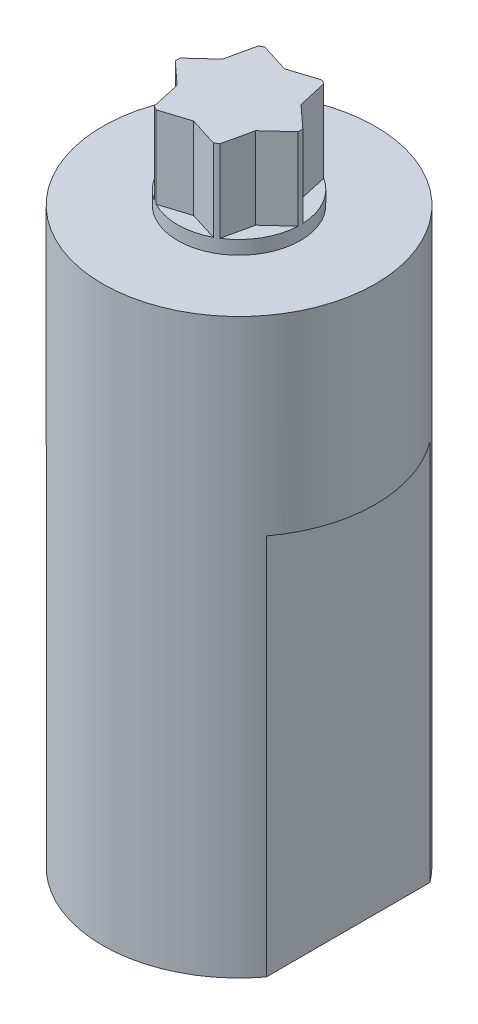
SolidWorks part; units mm, degrees
material "BUTYL"
ref_plane "Front Plane" through (0, 0, 0) normal (0, 0, 1) x (1, 0, 0)
ref_plane "Top Plane" through (0, 0, 0) normal (0, 1, 0) x (1, 0, 0)
ref_plane "Right Plane" through (0, 0, 0) normal (1, 0, 0) x (0, 0, -1)
sketch "Sketch1" plane through (0, 0, 0) normal (0, 1, 0) x (1, 0, 0)
  circle A0 centre (0, 0) radius 5
  dimension "D1" = 10
extrude "Boss-Extrude1" add sketch "Sketch1" along normal blind 7
sketch "Sketch2" plane through (0, 0, 0) normal (0, 1, 0) x (1, 0, 0)
  line L0 (-4, -3) -> (-4, 3)
  line L1 (4, -3) -> (4, 3)
  circle A0 centre (0, 0) radius 5 construction
  arc A1 (-4, -3) -> (4, -3) centre (0, 0) ccw
  arc A2 (4, 3) -> (-4, 3) centre (0, 0) ccw
  point P10 (0, 0)
  dimension "D1" = 8
extrude "Boss-Extrude2" add sketch "Sketch2" against normal blind 14 contours L1 A2 L0 A1
sketch "Sketch3" plane through (0, 7, 0) normal (0, 1, 0) x (1, 0, 0)
  circle A0 centre (0, 0) radius 2.25
  dimension "D1" = 4.5
extrude "Boss-Extrude3" add sketch "Sketch3" along normal blind 3.5
sketch "Sketch4" plane through (0, 10.5, 0) normal (0, 1, 0) x (1, 0, 0)
  line L0 (0, 1.6625) -> (-5.9097, 3.5218)
  line L1 (-5.9097, 3.5218) -> (5.9097, 3.5218)
  line L2 (5.9097, 3.5218) -> (0, 1.6625)
  point P2 (-1.2773, 3.0973)
  point P4 (2.3511, 3.2113)
  point P5 (0.3385, 1.0646)
  point P6 (0, 1.4192)
  point P7 (2.5919, 3.092)
  point P8 (0.6894, 1.7726)
  point P9 (0.7859, 1.7838)
  point P10 (0, 1.6023)
  point P11 (0, 1.2176)
  point P12 (0, 1.7273)
  point P13 (0, 0)
  point P14 (0, 1.194)
  point P15 (0, 1.6625)
extrude "Cut-Extrude1" cut sketch "Sketch4" against normal blind 3
pattern_circular "CirPattern1" count 6 over 360 about axis through (0, 0, 0) along (0, 1, 0) of "Cut-Extrude1"
